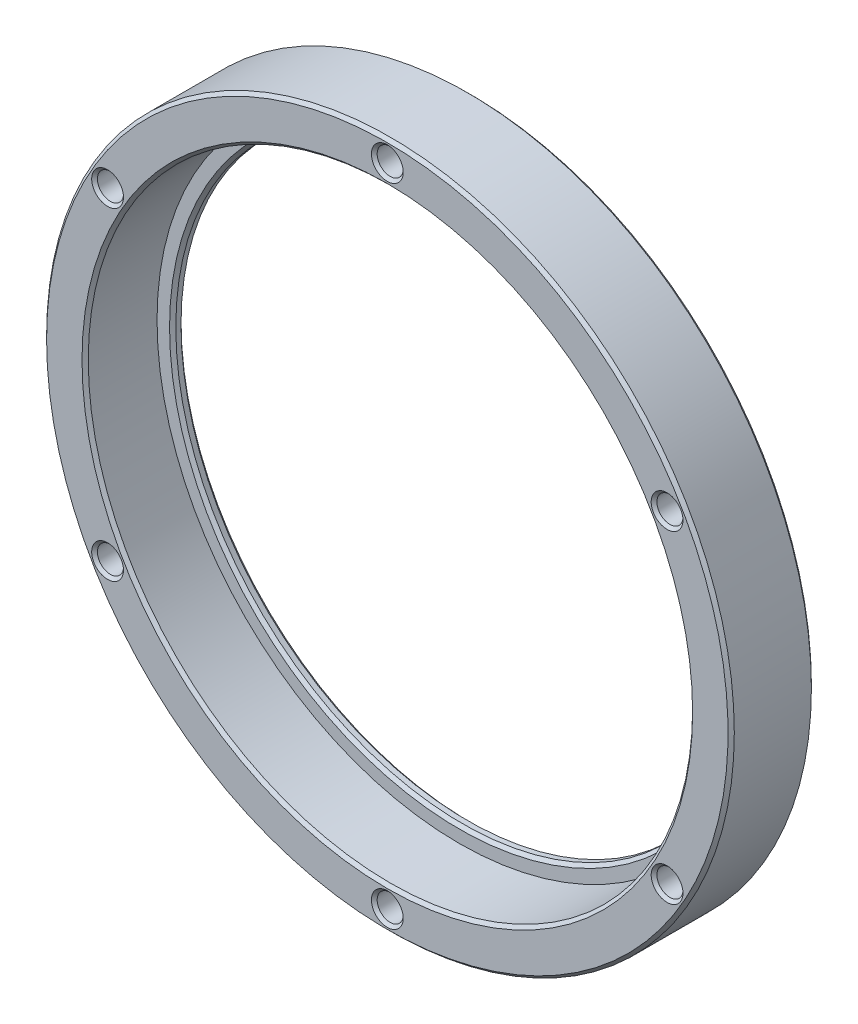
SolidWorks part; units mm, degrees
ref_plane "前视基准面" through (0, 0, 0) normal (0, 0, 1) x (1, 0, 0)
ref_plane "上视基准面" through (0, 0, 0) normal (0, 1, 0) x (1, 0, 0)
ref_plane "右视基准面" through (0, 0, 0) normal (1, 0, 0) x (0, 0, -1)
other "Configuration Table"
sketch "草图1" plane through (0, 0, 0) normal (0, 1, 0) x (1, 0, 0)
  line L0 (0, 0) -> (0, -33620.1676) construction
  line L1 (27.5, 0) -> (33, 0)
  line L2 (33, 0) -> (33, -8)
  line L3 (33, -8) -> (29, -8)
  line L4 (29, -8) -> (29, -1.1)
  line L5 (29, -1.1) -> (27.5, -1.1)
  line L6 (27.5, -1.1) -> (27.5, 0)
  dimension "D1" = 55
  dimension "D2" = 58
  dimension "D3" = 66
  dimension "D4" = 1.1
  dimension "D5" = 8
revolve "旋转1" add sketch "草图1" angle 360 about L0
hole_wizard "M3 螺纹孔1" positions "草图2" profile "草图3" tap size "M3" standard "GB" end condition through all
sketch "草图2" plane through (0, 0, 8) normal (0, 0, 1) x (1, 0, 0)
  circle A0 centre (0, 0) radius 31 construction
  point P0 (0, 31)
  dimension "D1" = 62
sketch "草图3" plane through (0, 31, 8) normal (1, 0, 0) x (0, -1, 0)
  line L0 (0, 0) -> (0, 8)
  line L1 (0, 8) -> (1.525, 8)
  line L2 (1.25, 7.725) -> (1.25, 0.275)
  line L3 (1.25, 0.275) -> (1.525, 0)
  line L5 (1.525, 0) -> (0, 0)
  line L6 (-1.25, 0.275) -> (-1.525, 0) construction
  line L7 (1.525, 8) -> (1.25, 7.725)
  line L8 (-1.525, 8) -> (-1.25, 7.725) construction
  line L11 (0, -6.35) -> (0, 107.95) construction
  dimension "通孔螺纹孔钻头直径" = 2.5
  dimension "通孔螺纹孔钻头深度" = 8
  dimension "近端锥形沉头孔直径" = 3.05
  dimension "近端锥形沉头孔角度" = 90
  dimension "远端锥形沉头孔直径" = 3.05
  dimension "远端锥形沉头孔角度" = 90
cosmetic thread "孔螺蚊线1" parameters "D2"=3
pattern_circular "阵列(圆周)1" count 6 over 360 about axis through (0, 0, 0) along (0, 0, 1) of "M3 螺纹孔1"
chamfer "倒角1" distance 0.3 angle 45 5 edges at (-27.5, 0, 0) (-27.5, 0, 1.1) (-33, 0, 8) (-33, 0, 0) (-29, 0, 8)
